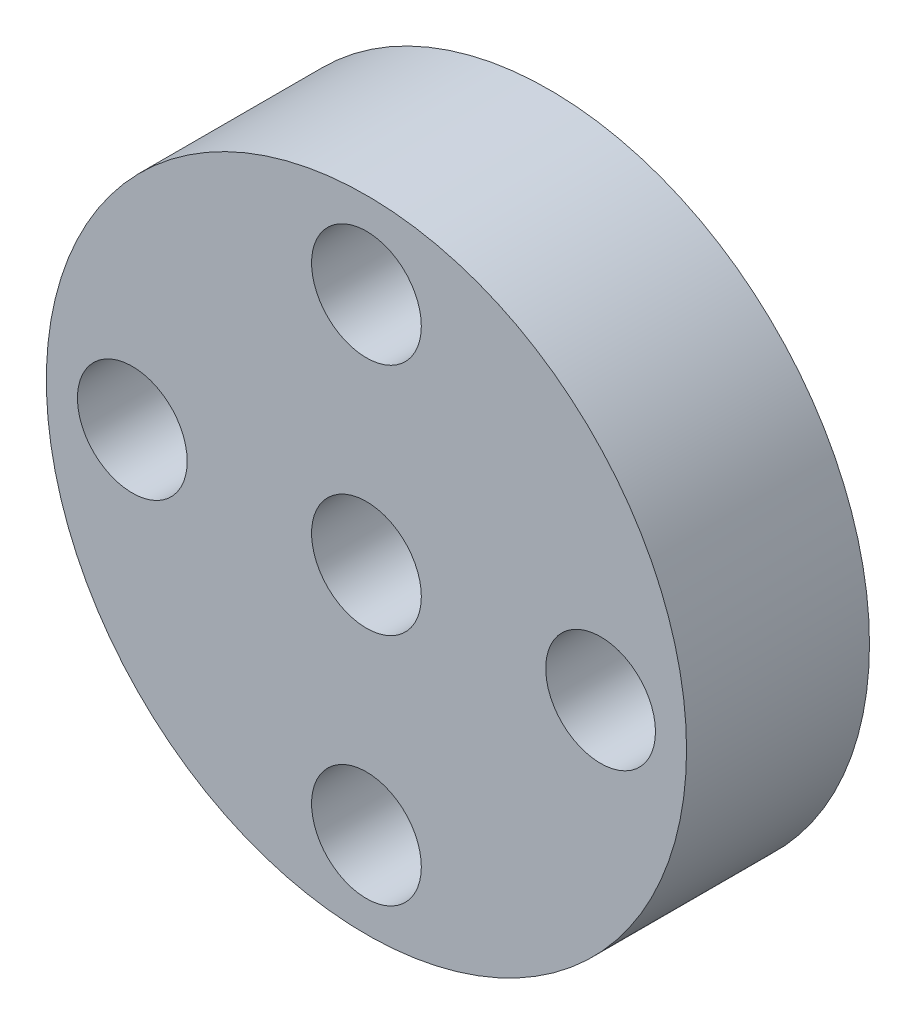
SolidWorks part; units mm, degrees
ref_plane "Front Plane" through (0, 0, 0) normal (0, 0, 1) x (1, 0, 0)
ref_plane "Top Plane" through (0, 0, 0) normal (0, 1, 0) x (1, 0, 0)
ref_plane "Right Plane" through (0, 0, 0) normal (1, 0, 0) x (0, 0, -1)
sketch "Sketch1" plane through (0, 0, 0) normal (0, 0, 1) x (1, 0, 0)
  circle A0 centre (0, 0) radius 8.75
  circle A1 centre (0, 0) radius 1.5
extrude "Extrude1" add sketch "Sketch1" along normal mid plane 5
sketch "Sketch2" plane through (0, 0, 0) normal (0, 0, 1) x (1, 0, 0)
  circle A0 centre (0, 0) radius 6.4 construction
  circle A1 centre (0, 6.4) radius 1.5
  circle A3 centre (6.4, 0) radius 1.5
  circle A4 centre (0, -6.4) radius 1.5
  circle A5 centre (-6.4, 0) radius 1.5
  point P14 (0, 0)
  dimension "D1" = 4
extrude "Extrude2" cut sketch "Sketch2" against normal through all both and the other way through all
